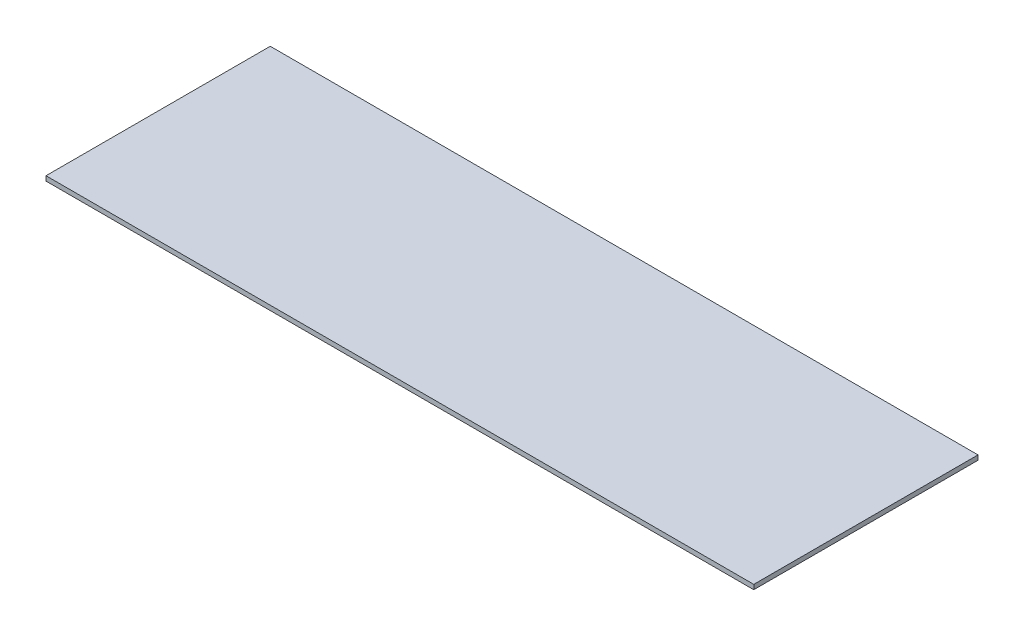
SolidWorks part; units mm, degrees
material "Pine"
ref_plane "Front Plane" through (0, 0, 0) normal (0, 0, 1) x (1, 0, 0)
ref_plane "Top Plane" through (0, 0, 0) normal (0, 1, 0) x (1, 0, 0)
ref_plane "Right Plane" through (0, 0, 0) normal (1, 0, 0) x (0, 0, -1)
sketch "Sketch1" plane through (0, 0, 0) normal (0, 1, 0) x (1, 0, 0)
  line L1 (240.5063, -76.2) -> (-240.5062, -76.2)
  line L2 (240.5063, -76.2) -> (240.5063, 76.2)
  line L3 (240.5063, 76.2) -> (-240.5062, 76.2)
  line L4 (-240.5062, -76.2) -> (-240.5062, 76.2)
  line L5 (240.5063, -76.2) -> (-240.5062, 76.2) construction
  line L6 (240.5063, 76.2) -> (-240.5062, -76.2) construction
  point P0 (0, 0)
  dimension "D1" = 481.0125
  dimension "D2" = 152.4
extrude "Boss-Extrude1" add sketch "Sketch1" along normal blind 3.175
